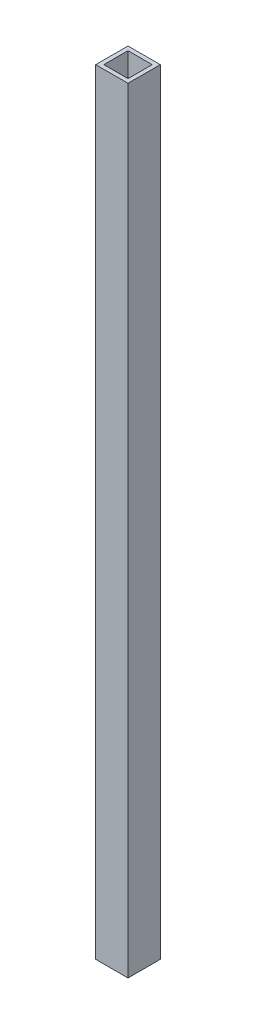
SolidWorks part; units mm, degrees
ref_plane "Front Plane" through (0, 0, 0) normal (0, 0, 1) x (1, 0, 0)
ref_plane "Top Plane" through (0, 0, 0) normal (0, 1, 0) x (1, 0, 0)
ref_plane "Right Plane" through (0, 0, 0) normal (1, 0, 0) x (0, 0, -1)
sketch "Sketch1" plane through (0, 0, 0) normal (0, 1, 0) x (1, 0, 0)
  line L0 (-9.525, 9.525) -> (9.525, 9.525)
  line L1 (-12.7, 12.7) -> (12.7, 12.7)
  line L2 (-12.7, 12.7) -> (-12.7, -12.7)
  line L3 (-12.7, -12.7) -> (12.7, -12.7)
  line L4 (12.7, 12.7) -> (12.7, -12.7)
  line L5 (9.525, 9.525) -> (9.525, -9.525)
  line L6 (-9.525, -9.525) -> (9.525, -9.525)
  line L7 (-9.525, 9.525) -> (-9.525, -9.525)
  point P7 (-11.5879, -4.4095)
  point P8 (13.8121, -1.4698)
  dimension "D1" = 25.4
  dimension "D2" = 25.4
  dimension "D3" = 12.7
  dimension "D4" = 12.7
  dimension "D5" = 3.175
extrude "Boss-Extrude1" add sketch "Sketch1" along normal blind 609.6
